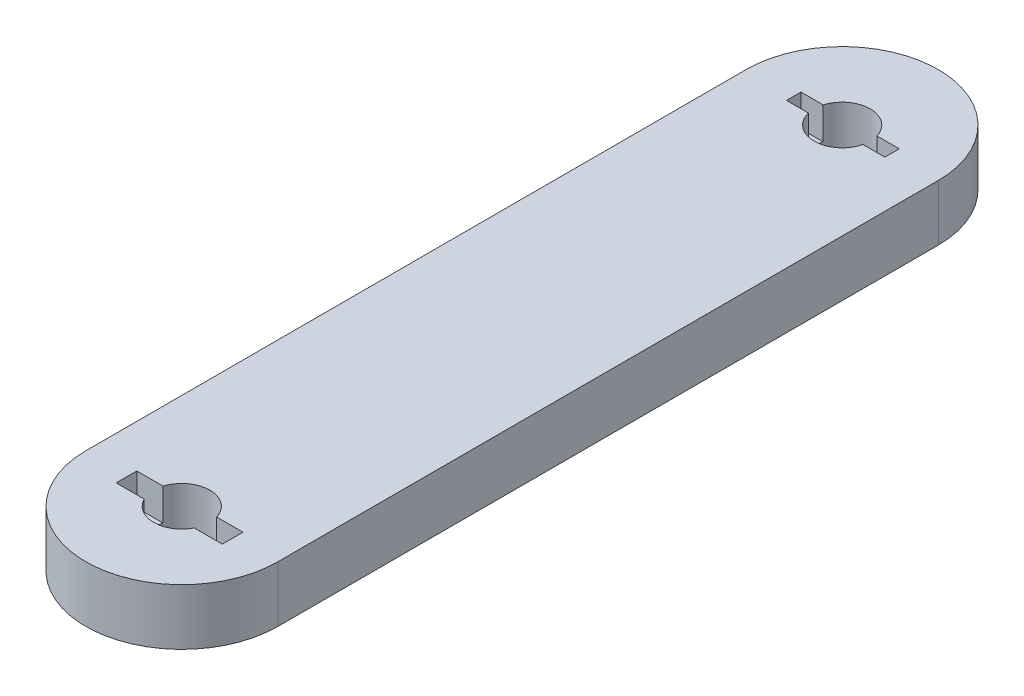
SolidWorks part; units mm, degrees
ref_plane "Front Plane" through (0, 0, 0) normal (0, 0, 1) x (1, 0, 0)
ref_plane "Top Plane" through (0, 0, 0) normal (0, 1, 0) x (1, 0, 0)
ref_plane "Right Plane" through (0, 0, 0) normal (1, 0, 0) x (0, 0, -1)
sketch "Sketch1" plane through (0, 0, 0) normal (0, 1, 0) x (1, 0, 0)
  line L0 (0, 24.7376) -> (0, -24.7376) construction
  line L1 (-28.1521, 0) -> (28.1521, 0) construction
  line L2 (-12, 41.25) -> (-12, -41.25)
  line L3 (12, 41.25) -> (12, -41.25)
  circle A0 centre (0, 41.25) radius 3.5
  circle A1 centre (0, -41.25) radius 3.5
  arc A2 (12, 41.25) -> (-12, 41.25) centre (0, 41.25) ccw
  arc A3 (-12, -41.25) -> (12, -41.25) centre (0, -41.25) ccw
  point P3 (0, 0)
  point P7 (0, 0)
  point P17 (12, 0)
  dimension "D1" = 7
  dimension "D2" = 24
  dimension "D3" = 7
  dimension "D4" = 24
  dimension "D5" = 82.5
extrude "Boss-Extrude1" add sketch "Sketch1" along normal blind 7
sketch "Sketch2" plane through (0, 7, 0) normal (0, 1, 0) x (1, 0, 0)
  line L0 (0, 44.75) -> (0, 37.75) construction
  line L5 (-6.6328, -40.233) -> (6.6239, -40.233)
  line L6 (-6.6328, -40.233) -> (-6.6328, -42.8139)
  line L7 (-6.6328, -42.8139) -> (6.6239, -42.8139)
  line L8 (6.6239, -40.233) -> (6.6239, -42.8139)
  line L9 (-3.5, 41.25) -> (3.5, 41.25) construction
  line L10 (8.0914, -41.5606) -> (-9.2728, -41.5606) construction
  line L12 (-6.1383, 42.2359) -> (6.1383, 42.2359)
  line L13 (-6.1383, 42.2359) -> (-6.1383, 40.4359)
  line L14 (-6.1383, 40.4359) -> (6.1383, 40.4359)
  line L15 (6.1383, 42.2359) -> (6.1383, 40.4359)
  circle A2 centre (0, 41.25) radius 3.5 construction
  point P2 (0, 41.25)
  point P10 (0, 42.2359)
  point P19 (6.1383, 41.3359)
  dimension "D1" = 12.2766
  dimension "D2" = 1.8
extrude "Cut-Extrude1" cut sketch "Sketch2" against normal blind 4
